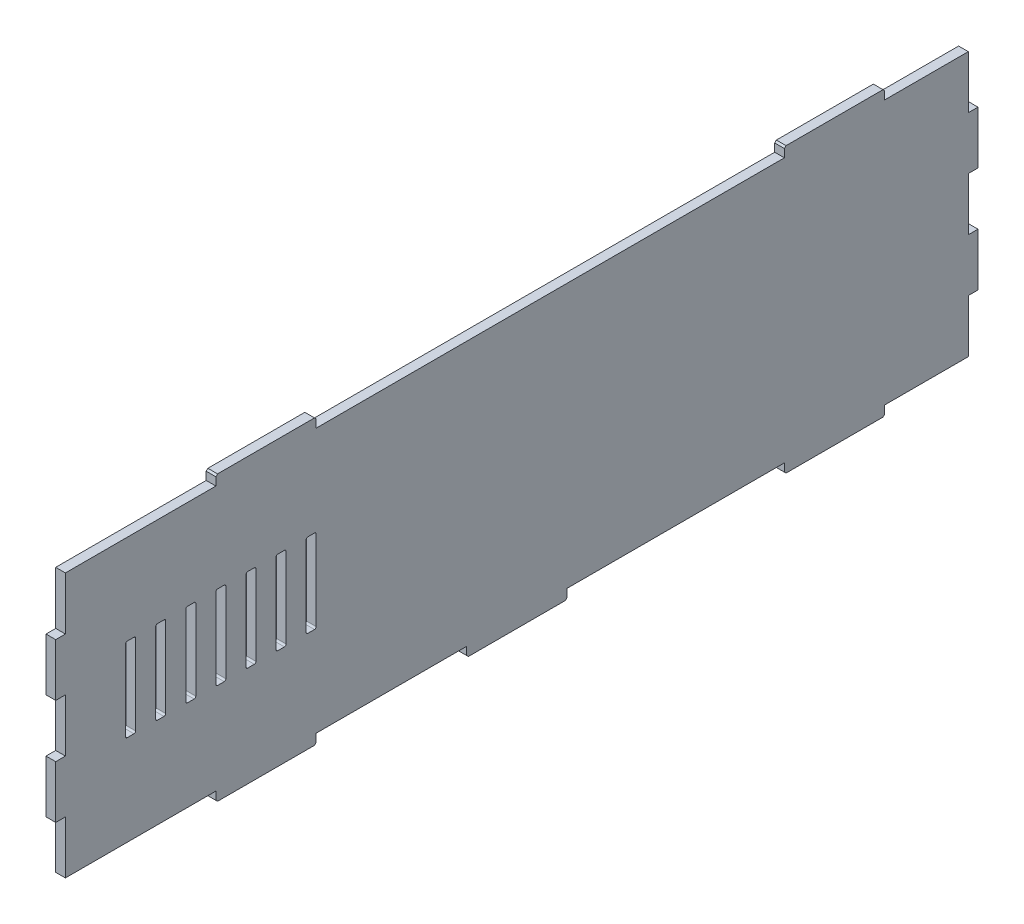
SolidWorks part; units mm, degrees
material "Acrylic (Medium-high impact)"
ref_plane "Front Plane" through (0, 0, 0) normal (0, 0, 1) x (1, 0, 0)
ref_plane "Top Plane" through (0, 0, 0) normal (0, 1, 0) x (1, 0, 0)
ref_plane "Right Plane" through (0, 0, 0) normal (1, 0, 0) x (0, 0, -1)
ref_plane "Plane1" through (-118.9, 0, 0) normal (1, 0, 0) x (0, 0, -1)
sketch "Sketch1" plane through (-118.9, 0, 0) normal (1, 0, 0) x (0, 0, -1)
  line L0 (135, 2.9) -> (110, 2.9)
  line L1 (110, 2.9) -> (110, 0.5)
  line L2 (110, 0.5) -> (109.5, 0)
  line L3 (109.5, 0) -> (80.5, 0)
  line L4 (80.5, 0) -> (80, 0.5)
  line L5 (80, 0.5) -> (80, 2.9)
  line L6 (80, 2.9) -> (15, 2.9)
  line L7 (15, 2.9) -> (15, 0.5)
  line L8 (15, 0.5) -> (14.5, 0)
  line L9 (14.5, 0) -> (-14.5, 0)
  line L10 (-14.5, 0) -> (-15, 0.5)
  line L11 (-15, 0.5) -> (-15, 2.9)
  line L12 (-15, 2.9) -> (-60, 2.9)
  line L13 (-60, 2.9) -> (-60, 0.5)
  line L14 (-60, 0.5) -> (-60.5, 0)
  line L15 (-60.5, 0) -> (-89.5, 0)
  line L16 (-89.5, 0) -> (-90, 0.5)
  line L17 (-90, 0.5) -> (-90, 2.9)
  line L18 (-90, 2.9) -> (-135, 2.9)
  line L19 (-135, 2.9) -> (-135, 18.725)
  line L20 (-135, 18.725) -> (-137.9, 18.725)
  line L21 (-137.9, 18.725) -> (-137.9, 34.475)
  line L22 (-137.9, 34.475) -> (-135, 34.475)
  line L23 (-135, 34.475) -> (-135, 50.325)
  line L24 (-135, 50.325) -> (-137.9, 50.325)
  line L25 (-137.9, 50.325) -> (-137.9, 66.075)
  line L26 (-137.9, 66.075) -> (-135, 66.075)
  line L27 (-135, 66.075) -> (-135, 81.9)
  line L28 (-135, 81.9) -> (-90, 81.9)
  line L29 (-90, 81.9) -> (-90, 84.3)
  line L30 (-90, 84.3) -> (-89.5, 84.8)
  line L31 (-89.5, 84.8) -> (-60.5, 84.8)
  line L32 (-60.5, 84.8) -> (-60, 84.3)
  line L33 (-60, 84.3) -> (-60, 81.9)
  line L34 (-60, 81.9) -> (80, 81.9)
  line L35 (80, 81.9) -> (80, 84.3)
  line L36 (80, 84.3) -> (80.5, 84.8)
  line L37 (80.5, 84.8) -> (109.5, 84.8)
  line L38 (109.5, 84.8) -> (110, 84.3)
  line L39 (110, 84.3) -> (110, 81.9)
  line L40 (110, 81.9) -> (135, 81.9)
  line L41 (135, 81.9) -> (135, 66.075)
  line L42 (135, 66.075) -> (137.9, 66.075)
  line L43 (137.9, 66.075) -> (137.9, 50.325)
  line L44 (137.9, 50.325) -> (135, 50.325)
  line L45 (135, 50.325) -> (135, 34.475)
  line L46 (135, 34.475) -> (137.9, 34.475)
  line L47 (137.9, 34.475) -> (137.9, 18.725)
  line L48 (137.9, 18.725) -> (135, 18.725)
  line L49 (135, 18.725) -> (135, 2.9)
  line L50 (-114.5, 30) -> (-116.5, 30)
  line L51 (-117, 30.5) -> (-117, 54.5)
  line L52 (-116.5, 55) -> (-114.5, 55)
  line L53 (-114, 54.5) -> (-114, 30.5)
  line L54 (-105.5, 30) -> (-107.5, 30)
  line L55 (-108, 30.5) -> (-108, 54.5)
  line L56 (-107.5, 55) -> (-105.5, 55)
  line L57 (-105, 54.5) -> (-105, 30.5)
  line L58 (-96.5, 30) -> (-98.5, 30)
  line L59 (-99, 30.5) -> (-99, 54.5)
  line L60 (-98.5, 55) -> (-96.5, 55)
  line L61 (-96, 54.5) -> (-96, 30.5)
  line L62 (-87.5, 30) -> (-89.5, 30)
  line L63 (-90, 30.5) -> (-90, 54.5)
  line L64 (-89.5, 55) -> (-87.5, 55)
  line L65 (-87, 54.5) -> (-87, 30.5)
  line L66 (-78.5, 30) -> (-80.5, 30)
  line L67 (-81, 30.5) -> (-81, 54.5)
  line L68 (-80.5, 55) -> (-78.5, 55)
  line L69 (-78, 54.5) -> (-78, 30.5)
  line L70 (-69.5, 30) -> (-71.5, 30)
  line L71 (-72, 30.5) -> (-72, 54.5)
  line L72 (-71.5, 55) -> (-69.5, 55)
  line L73 (-69, 54.5) -> (-69, 30.5)
  line L74 (-60.5, 30) -> (-62.5, 30)
  line L75 (-63, 30.5) -> (-63, 54.5)
  line L76 (-62.5, 55) -> (-60.5, 55)
  line L77 (-60, 54.5) -> (-60, 30.5)
  arc A0 (-114, 30.5) -> (-114.5, 30) centre (-114.5, 30.5) cw
  arc A1 (-116.5, 30) -> (-117, 30.5) centre (-116.5, 30.5) cw
  arc A2 (-117, 54.5) -> (-116.5, 55) centre (-116.5, 54.5) cw
  arc A3 (-114.5, 55) -> (-114, 54.5) centre (-114.5, 54.5) cw
  arc A4 (-105, 30.5) -> (-105.5, 30) centre (-105.5, 30.5) cw
  arc A5 (-107.5, 30) -> (-108, 30.5) centre (-107.5, 30.5) cw
  arc A6 (-108, 54.5) -> (-107.5, 55) centre (-107.5, 54.5) cw
  arc A7 (-105.5, 55) -> (-105, 54.5) centre (-105.5, 54.5) cw
  arc A8 (-96, 30.5) -> (-96.5, 30) centre (-96.5, 30.5) cw
  arc A9 (-98.5, 30) -> (-99, 30.5) centre (-98.5, 30.5) cw
  arc A10 (-99, 54.5) -> (-98.5, 55) centre (-98.5, 54.5) cw
  arc A11 (-96.5, 55) -> (-96, 54.5) centre (-96.5, 54.5) cw
  arc A12 (-87, 30.5) -> (-87.5, 30) centre (-87.5, 30.5) cw
  arc A13 (-89.5, 30) -> (-90, 30.5) centre (-89.5, 30.5) cw
  arc A14 (-90, 54.5) -> (-89.5, 55) centre (-89.5, 54.5) cw
  arc A15 (-87.5, 55) -> (-87, 54.5) centre (-87.5, 54.5) cw
  arc A16 (-78, 30.5) -> (-78.5, 30) centre (-78.5, 30.5) cw
  arc A17 (-80.5, 30) -> (-81, 30.5) centre (-80.5, 30.5) cw
  arc A18 (-81, 54.5) -> (-80.5, 55) centre (-80.5, 54.5) cw
  arc A19 (-78.5, 55) -> (-78, 54.5) centre (-78.5, 54.5) cw
  arc A20 (-69, 30.5) -> (-69.5, 30) centre (-69.5, 30.5) cw
  arc A21 (-71.5, 30) -> (-72, 30.5) centre (-71.5, 30.5) cw
  arc A22 (-72, 54.5) -> (-71.5, 55) centre (-71.5, 54.5) cw
  arc A23 (-69.5, 55) -> (-69, 54.5) centre (-69.5, 54.5) cw
  arc A24 (-60, 30.5) -> (-60.5, 30) centre (-60.5, 30.5) cw
  arc A25 (-62.5, 30) -> (-63, 30.5) centre (-62.5, 30.5) cw
  arc A26 (-63, 54.5) -> (-62.5, 55) centre (-62.5, 54.5) cw
  arc A27 (-60.5, 55) -> (-60, 54.5) centre (-60.5, 54.5) cw
extrude "Boss-Extrude1" add sketch "Sketch1" along normal blind 2.9
